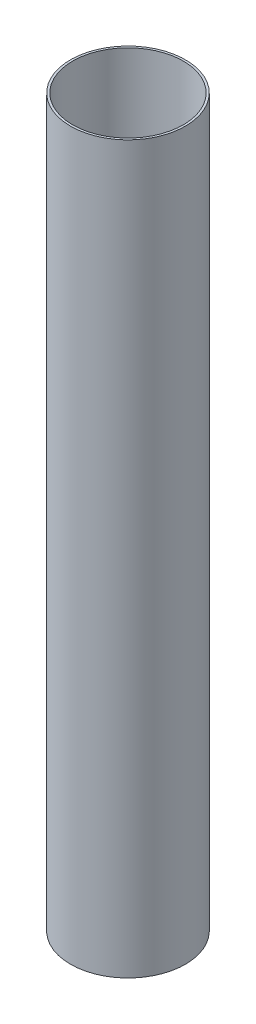
SolidWorks part; units mm, degrees
ref_plane "Front Plane" through (0, 0, 0) normal (0, 0, 1) x (1, 0, 0)
ref_plane "Top Plane" through (0, 0, 0) normal (0, 1, 0) x (1, 0, 0)
ref_plane "Right Plane" through (0, 0, 0) normal (1, 0, 0) x (0, 0, -1)
sketch "Sketch1" plane through (0, 0, 0) normal (0, 1, 0) x (1, 0, 0)
  circle A0 centre (0, 0) radius 38.1
  circle A1 centre (0, 0) radius 39.6
  dimension "D1" = 76.2
  dimension "D2" = 1.5
extrude "Boss-Extrude1" add sketch "Sketch1" along normal blind 500
sketch "Sketch2" plane through (0, 0, 0) normal (1, 0, 0) x (0, 0, -1)
  line L0 (39.6, 500) -> (-39.6, 500) construction
  circle A0 centre (0, 289) radius 2
  dimension "D1" = 4
  dimension "D2" = 211
extrude "Cut-Extrude1" cut sketch "Sketch2" against normal up to surface (39.5495 mm away)
